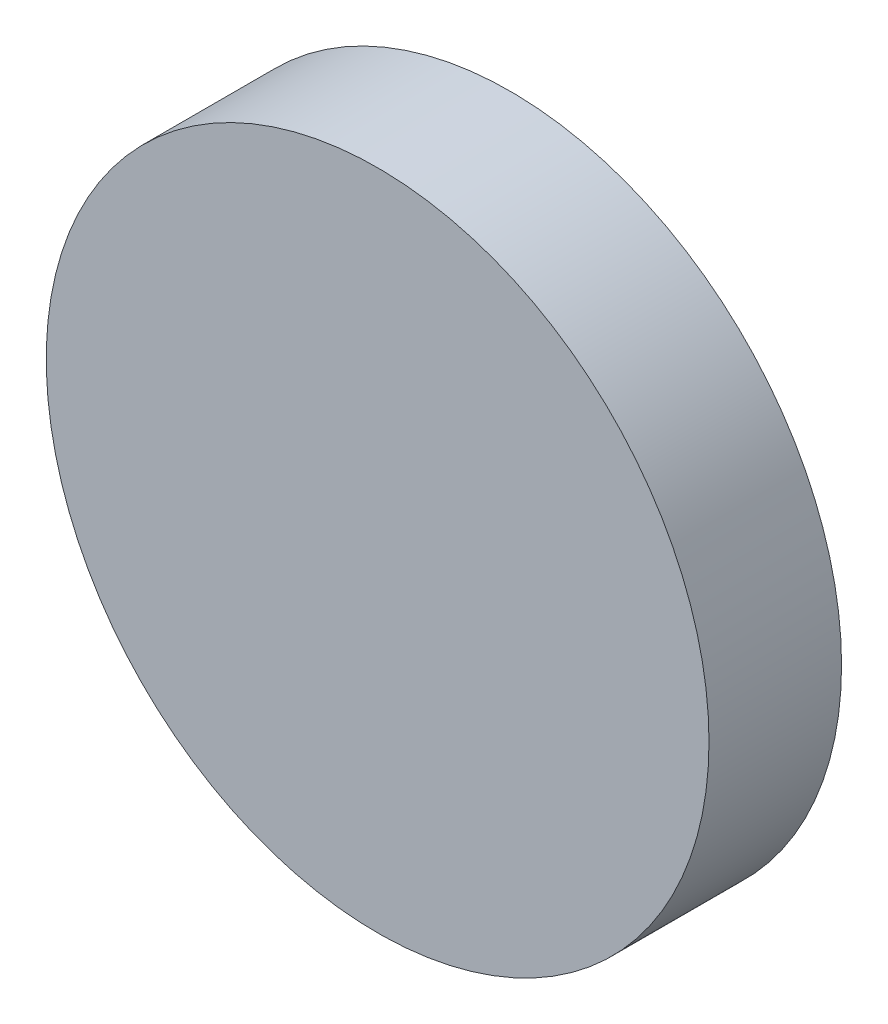
SolidWorks part; units mm, degrees
ref_plane "Front Plane" through (0, 0, 0) normal (0, 0, 1) x (1, 0, 0)
ref_plane "Top Plane" through (0, 0, 0) normal (0, 1, 0) x (1, 0, 0)
ref_plane "Right Plane" through (0, 0, 0) normal (1, 0, 0) x (0, 0, -1)
sketch "Sketch1" plane through (0, 0, 0) normal (0, 0, 1) x (1, 0, 0)
  circle A0 centre (-62.3906, -116) radius 7.5
extrude "Boss-Extrude1" add sketch "Sketch1" against normal blind 3
